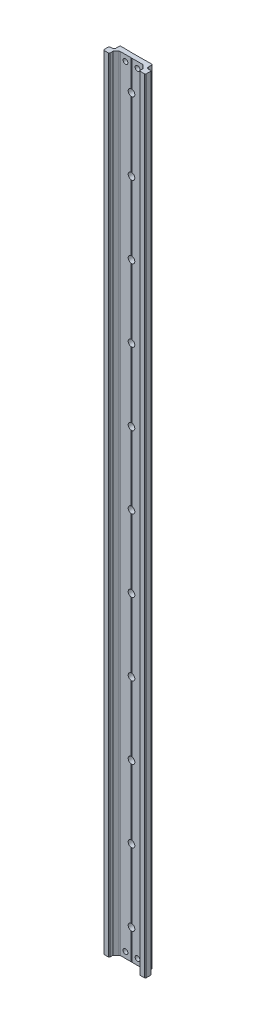
SolidWorks part; units mm, degrees
ref_plane "Plan de face" through (0, 0, 0) normal (0, 0, 1) x (1, 0, 0)
ref_plane "Plan de dessus" through (0, 0, 0) normal (0, 1, 0) x (1, 0, 0)
ref_plane "Plan de droite" through (0, 0, 0) normal (1, 0, 0) x (0, 0, -1)
ref_plane "Plan1" through (0, 325, 0) normal (0, 1, 0) x (1, 0, 0)
sketch "Esquisse1" plane through (0, 325, 0) normal (0, 1, 0) x (1, 0, 0)
  line L0 (-9.7, 1) -> (9.7, 1)
  line L1 (9.7, 1) -> (12.5, -1.8)
  line L2 (12.5, -1.8) -> (12.5, -5)
  line L3 (12.5, -5) -> (17.5, -5)
  line L4 (17.5, -5) -> (17.5, 5)
  line L5 (17.5, 5) -> (-17.5, 5)
  line L6 (-17.5, 5) -> (-17.5, -5)
  line L7 (-17.5, -5) -> (-12.5, -5)
  line L8 (-12.5, -5) -> (-12.5, -1.8)
  line L9 (-12.5, -1.8) -> (-9.7, 1)
extrude "Boss.-Extru.1" add sketch "Esquisse1" against normal blind 650
sketch "Esquisse2" plane through (0, -325, 0) normal (0, -1, 0) x (1, 0, 0)
  line L0 (-14.3, 0) -> (-17.5, 0)
  line L1 (-17.5, 0) -> (-17.5, -5)
  line L2 (-17.5, -5) -> (-13.5, -5)
  line L3 (-13.5, -5) -> (-13.5, -0.8)
  line L4 (-13.5, -0.8) -> (-14.3, 0)
extrude "Enlèv. mat.-Extru.1" cut sketch "Esquisse2" against normal through all
sketch "Esquisse3" plane through (0, -325, 0) normal (0, -1, 0) x (1, 0, 0)
  line L0 (0.25, -1) -> (-0.25, -1)
  line L1 (-0.25, -1) -> (0, -1.1443)
  line L2 (0, -1.1443) -> (0.25, -1)
extrude "Enlèv. mat.-Extru.2" cut sketch "Esquisse3" against normal blind 650
sketch "Esquisse4" plane through (0, -325, 0) normal (0, -1, 0) x (1, 0, 0)
  line L0 (13.5, -0.8) -> (13.5, -5)
  line L1 (13.5, -5) -> (17.5, -5)
  line L2 (17.5, -5) -> (17.5, 0)
  line L3 (17.5, 0) -> (14.3, 0)
  line L4 (14.3, 0) -> (13.5, -0.8)
extrude "Enlèv. mat.-Extru.3" cut sketch "Esquisse4" against normal through all
sketch "Esquisse5" plane through (0, -325, 0) normal (0, -1, 0) x (1, 0, 0)
  line L0 (-7.5, -5) -> (7.5, -5)
  line L1 (7.5, -5) -> (7.4, -4.9)
  line L2 (7.4, -4.9) -> (-7.4, -4.9)
  line L3 (-7.4, -4.9) -> (-7.5, -5)
extrude "Enlèv. mat.-Extru.4" cut sketch "Esquisse5" against normal blind 650
hole_wizard "Diamètre du perçage Ø5.5 (5.5)1" positions "Esquisse7" profile "Esquisse6" hole size "Ø5.5" standard "Ansi Metric"
sketch "Esquisse7" plane through (0, 0, -4.9) normal (0, 0, -1) x (-1, 0, 0)
  point P0 (0, 300)
  point P1 (0, 240)
  point P2 (0, 180)
  point P3 (0, 120)
  point P4 (0, 60)
  point P5 (0, 0)
  point P6 (0, -60)
  point P7 (0, -120)
  point P8 (0, -180)
  point P9 (0, -240)
  point P10 (0, -300)
sketch "Esquisse6" plane through (0, 300, -4.9) normal (1, 0, 0) x (0, 1, 0)
  line L0 (0, 0) -> (0, 9.9)
  line L1 (0, 9.9) -> (2.75, 9.9)
  line L2 (2.75, 9.9) -> (2.75, 0)
  line L5 (2.75, 0) -> (0, 0)
  line L11 (0, -6.35) -> (0, 107.95) construction
  dimension "Diamètre du perçage jusqu'au prochain" = 5.5
  dimension "Profondeur du perçage jusqu'au prochain" = 9.9
chamfer "Chanfrein1" distance 0.5 angle 45 2 edges at (17.5, 0, 5) (-17.5, 0, 5)
chamfer "Chanfrein2" distance 0.3 angle 45 2 edges at (-13.5, 0, -5) (13.5, 0, -5)
chamfer "Chanfrein3" distance 0.5 angle 45 3 edges at (12.5, 0, 5) (-17.5, 0, 0) (-12.5, 0, 5)
chamfer "Chanfrein4" distance 0.5 angle 45 1 edges at (17.5, 0, 0)
fillet "Congé1" radius 1.5 2 edges at (9.7, 0, -1) (-9.7, 0, -1)
fillet "Congé2" radius 2 2 edges at (13.5, 0, -0.8) (-13.5, 0, -0.8)
sketch "Esquisse8" plane through (0, 0, -1) normal (0, 0, 1) x (1, 0, 0)
  line L0 (-9.0787, -325) -> (-0.25, -325) construction
  line L1 (0.25, -325) -> (9.0787, -325) construction
  line L2 (-9.0787, 325) -> (-0.25, 325) construction
  line L3 (0.25, 325) -> (9.0787, 325) construction
  line L4 (0, 325) -> (0, 302.75) construction
  circle A0 centre (-5, -320) radius 2
  circle A1 centre (5, -320) radius 2
  circle A2 centre (-5, 320) radius 2
  circle A3 centre (5, 320) radius 2
  dimension "D1" = 4
  dimension "D2" = 4
  dimension "D3" = 4
  dimension "D4" = 4
  dimension "D5" = 5
  dimension "D6" = 5
  dimension "D7" = 5
  dimension "D8" = 5
  dimension "D9" = 5
  dimension "D10" = 5
  dimension "D11" = 5
  dimension "D12" = 5
extrude "Enlèv. mat.-Extru.5" cut sketch "Esquisse8" against normal blind 10
